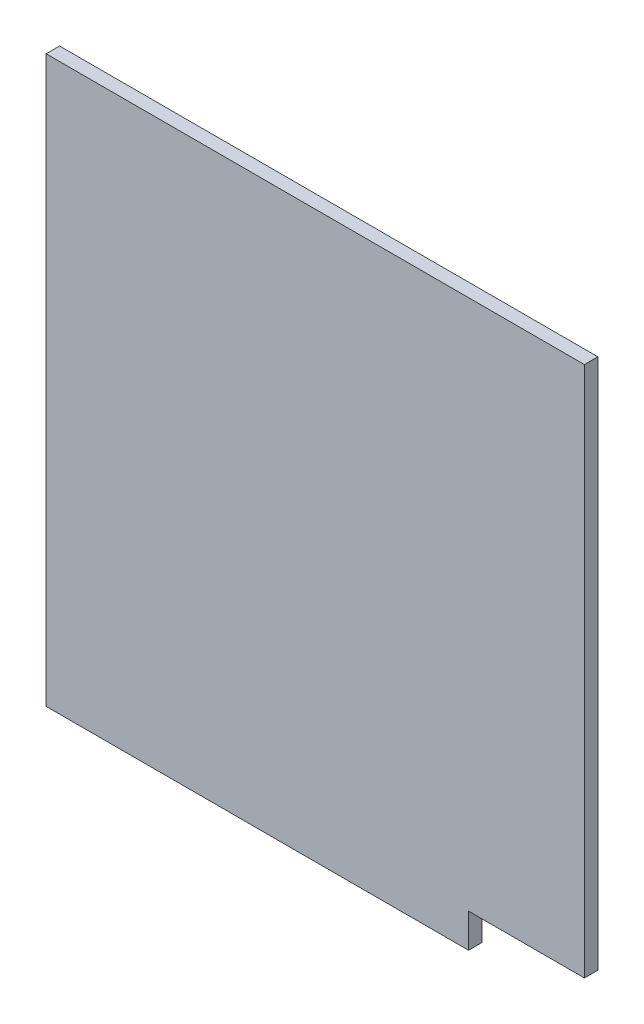
SolidWorks part; units mm, degrees
ref_plane "Front Plane" through (0, 0, 0) normal (0, 0, 1) x (1, 0, 0)
ref_plane "Top Plane" through (0, 0, 0) normal (0, 1, 0) x (1, 0, 0)
ref_plane "Right Plane" through (0, 0, 0) normal (1, 0, 0) x (0, 0, -1)
sketch "Sketch1" plane through (0, 0, 0) normal (0, 0, 1) x (1, 0, 0)
  line L1 (4.7625, 0) -> (195.2375, 0)
  line L2 (4.7625, 0) -> (4.7625, -200)
  line L3 (4.7625, -200) -> (195.2375, -200)
  line L4 (195.2375, 0) -> (195.2375, -200)
  line L5 (195.2375, -200) -> (154.2375, -200)
  line L6 (195.2375, -200) -> (195.2375, -188)
  line L7 (195.2375, -188) -> (154.2375, -188)
  line L8 (154.2375, -200) -> (154.2375, -188)
  dimension "D1" = 41
  dimension "D2" = 12
extrude "Boss-Extrude1" add sketch "Sketch1" against normal blind 4.7625 contours L3 L8 L7 L4 L1 L2
